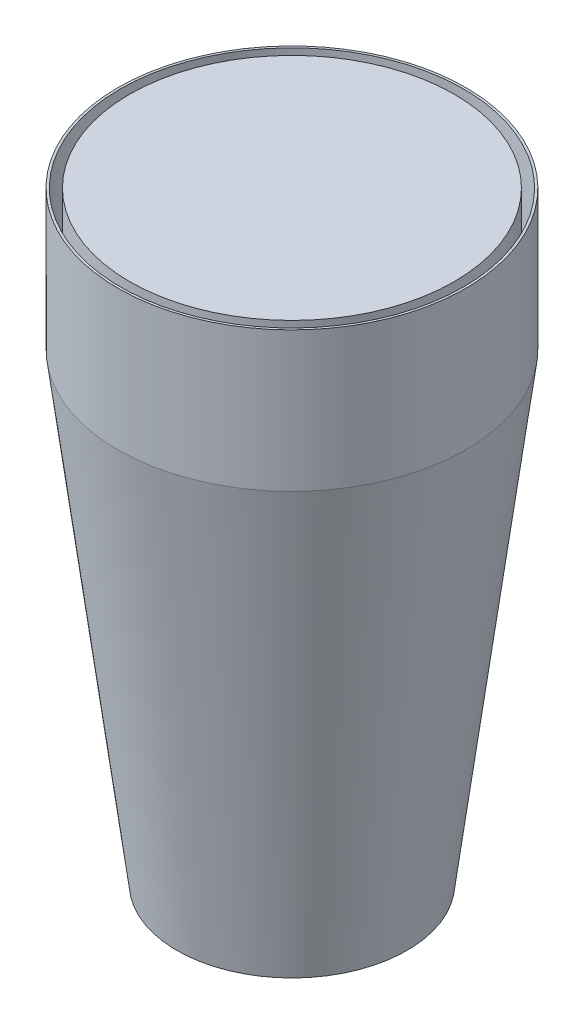
SolidWorks part; units mm, degrees
ref_plane "Front Plane" through (0, 0, 0) normal (0, 0, 1) x (1, 0, 0)
ref_plane "Top Plane" through (0, 0, 0) normal (0, 1, 0) x (1, 0, 0)
ref_plane "Right Plane" through (0, 0, 0) normal (1, 0, 0) x (0, 0, -1)
sketch "Sketch1" plane through (0, 0, 0) normal (0, 0, 1) x (1, 0, 0)
  line L0 (0, 0) -> (45, 0)
  line L1 (45, 0) -> (45, 200)
  line L2 (45, 200) -> (70, 200)
  line L3 (70, 200) -> (70, 260)
  line L4 (70, 260) -> (0, 260)
  line L5 (0, 260) -> (0, 0)
  dimension "D1" = 45
  dimension "D2" = 70
  dimension "D3" = 60
  dimension "D4" = 200
revolve "rough engine" add sketch "Sketch1" angle 360 about L5
sketch "Sketch2" plane through (0, 0, 0) normal (0, 0, 1) x (1, 0, 0)
  line L0 (0, 260) -> (0, 0) construction
  line L1 (70, 260) -> (-70, 260) construction
  line L2 (75, 260) -> (75, 199.6837)
  line L3 (75, 199.6837) -> (49.6384, 0)
  line L4 (74, 260) -> (74, 199.747)
  line L5 (74, 199.747) -> (48.6304, 0)
  line L6 (74, 260) -> (75, 260)
  line L7 (48.6304, 0) -> (49.6384, 0) construction
  line L8 (48.6304, 0) -> (49.6384, 0)
  line L10 (74, 199.747) -> (48.5664, -0.504) construction
  line L11 (75, 199.6837) -> (49.5584, -0.63) construction
  dimension "D1" = 1
revolve "Revolve2" add sketch "Sketch2" angle 360 about L0
